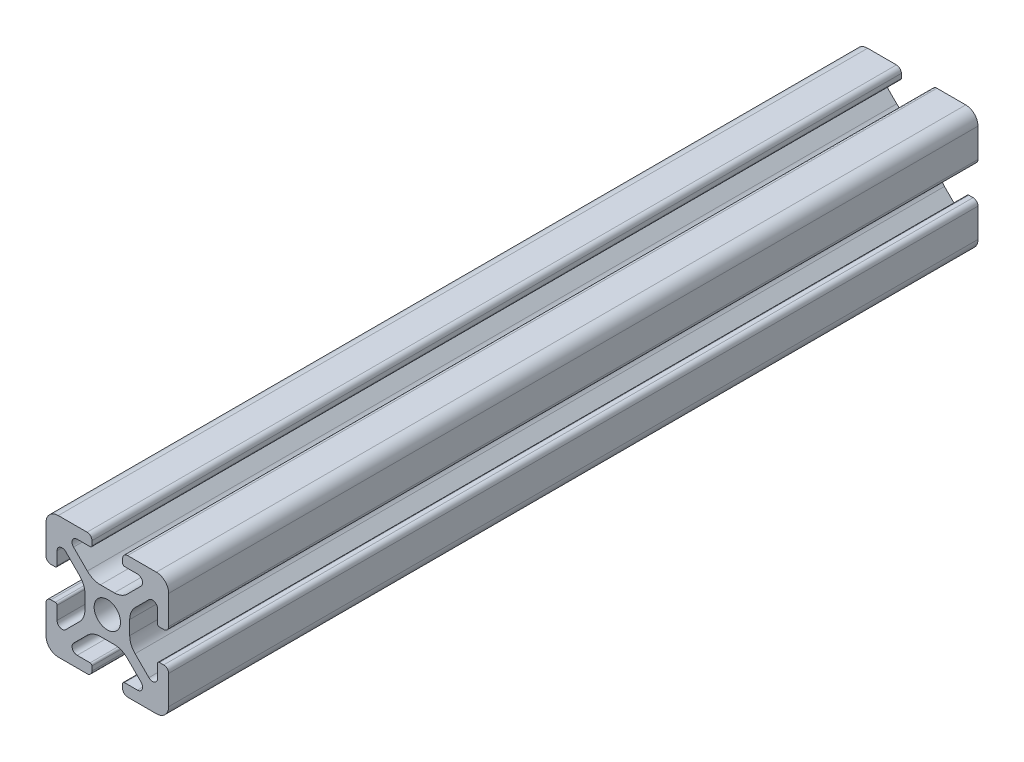
SolidWorks part; units mm, degrees
material "Alliage 1060"
ref_plane "Plan de face" through (0, 0, 0) normal (0, 0, 1) x (1, 0, 0)
ref_plane "Plan de dessus" through (0, 0, 0) normal (0, 1, 0) x (1, 0, 0)
ref_plane "Plan de droite" through (0, 0, 0) normal (1, 0, 0) x (0, 0, -1)
sketch "Esquisse1" plane through (0, 0, 0) normal (0, 0, 1) x (1, 0, 0)
  line L108 (-3.2559, 4.5287) -> (-5.5062, 6.779)
  line L109 (-4.9176, 8.2) -> (-2.8, 8.2)
  line L110 (-2.5, 8.5) -> (-2.5, 9.2)
  line L111 (-3.3, 10) -> (-8, 10)
  line L112 (-10, 8) -> (-10, 3.3)
  line L113 (-9.2, 2.5) -> (-8.5, 2.5)
  line L114 (-8.2, 2.8) -> (-8.2, 4.9176)
  line L115 (-6.779, 5.5062) -> (-4.5287, 3.2559)
  line L116 (-3.65, 1.1346) -> (-3.65, -1.1346)
  line L117 (-4.5287, -3.2559) -> (-6.779, -5.5062)
  line L118 (-8.2, -4.9176) -> (-8.2, -2.8)
  line L119 (-8.5, -2.5) -> (-9.2, -2.5)
  line L120 (-10, -3.3) -> (-10, -8)
  line L121 (-8, -10) -> (-3.3, -10)
  line L122 (-2.5, -9.2) -> (-2.5, -8.5)
  line L123 (-2.8, -8.2) -> (-4.9176, -8.2)
  line L124 (-5.5062, -6.779) -> (-3.2559, -4.5287)
  line L125 (-1.1346, -3.65) -> (1.1346, -3.65)
  line L126 (3.2559, -4.5287) -> (5.5062, -6.779)
  line L127 (4.9176, -8.2) -> (2.8, -8.2)
  line L128 (2.5, -8.5) -> (2.5, -9.2)
  line L129 (3.3, -10) -> (8, -10)
  line L130 (10, -8) -> (10, -3.3)
  line L131 (9.2, -2.5) -> (8.5, -2.5)
  line L132 (8.2, -2.8) -> (8.2, -4.9176)
  line L133 (6.779, -5.5062) -> (4.5287, -3.2559)
  line L134 (3.65, -1.1346) -> (3.65, 1.1346)
  line L135 (4.5287, 3.2559) -> (6.779, 5.5062)
  line L136 (8.2, 4.9176) -> (8.2, 2.8)
  line L137 (8.5, 2.5) -> (9.2, 2.5)
  line L138 (10, 3.3) -> (10, 8)
  line L139 (8, 10) -> (3.3, 10)
  line L140 (2.5, 9.2) -> (2.5, 8.5)
  line L141 (2.8, 8.2) -> (4.9176, 8.2)
  line L142 (5.5062, 6.779) -> (3.2559, 4.5287)
  line L143 (1.1346, 3.65) -> (-1.1346, 3.65)
  arc A42 (-2.15, 0) -> (2.15, 0) centre (0, 0) ccw
  arc A43 (2.15, 0) -> (-2.15, 0) centre (0, 0) ccw
  arc A108 (-4.9176, 8.2) -> (-5.5062, 6.779) centre (-4.9176, 7.3676) ccw
  arc A109 (-2.8, 8.2) -> (-2.5, 8.5) centre (-2.8, 8.5) ccw
  arc A110 (-2.5, 9.2) -> (-3.3, 10) centre (-3.3, 9.2) ccw
  arc A111 (-8, 10) -> (-10, 8) centre (-8, 8) ccw
  arc A112 (-10, 3.3) -> (-9.2, 2.5) centre (-9.2, 3.3) ccw
  arc A113 (-8.5, 2.5) -> (-8.2, 2.8) centre (-8.5, 2.8) ccw
  arc A114 (-6.779, 5.5062) -> (-8.2, 4.9176) centre (-7.3676, 4.9176) ccw
  arc A115 (-3.65, 1.1346) -> (-4.5287, 3.2559) centre (-6.65, 1.1346) ccw
  arc A116 (-4.5287, -3.2559) -> (-3.65, -1.1346) centre (-6.65, -1.1346) ccw
  arc A117 (-8.2, -4.9176) -> (-6.779, -5.5062) centre (-7.3676, -4.9176) ccw
  arc A118 (-8.2, -2.8) -> (-8.5, -2.5) centre (-8.5, -2.8) ccw
  arc A119 (-9.2, -2.5) -> (-10, -3.3) centre (-9.2, -3.3) ccw
  arc A120 (-10, -8) -> (-8, -10) centre (-8, -8) ccw
  arc A121 (-3.3, -10) -> (-2.5, -9.2) centre (-3.3, -9.2) ccw
  arc A122 (-2.5, -8.5) -> (-2.8, -8.2) centre (-2.8, -8.5) ccw
  arc A123 (-5.5062, -6.779) -> (-4.9176, -8.2) centre (-4.9176, -7.3676) ccw
  arc A124 (-1.1346, -3.65) -> (-3.2559, -4.5287) centre (-1.1346, -6.65) ccw
  arc A125 (3.2559, -4.5287) -> (1.1346, -3.65) centre (1.1346, -6.65) ccw
  arc A126 (4.9176, -8.2) -> (5.5062, -6.779) centre (4.9176, -7.3676) ccw
  arc A127 (2.8, -8.2) -> (2.5, -8.5) centre (2.8, -8.5) ccw
  arc A128 (2.5, -9.2) -> (3.3, -10) centre (3.3, -9.2) ccw
  arc A129 (8, -10) -> (10, -8) centre (8, -8) ccw
  arc A130 (10, -3.3) -> (9.2, -2.5) centre (9.2, -3.3) ccw
  arc A131 (8.5, -2.5) -> (8.2, -2.8) centre (8.5, -2.8) ccw
  arc A132 (6.779, -5.5062) -> (8.2, -4.9176) centre (7.3676, -4.9176) ccw
  arc A133 (3.65, -1.1346) -> (4.5287, -3.2559) centre (6.65, -1.1346) ccw
  arc A134 (4.5287, 3.2559) -> (3.65, 1.1346) centre (6.65, 1.1346) ccw
  arc A135 (8.2, 4.9176) -> (6.779, 5.5062) centre (7.3676, 4.9176) ccw
  arc A136 (8.2, 2.8) -> (8.5, 2.5) centre (8.5, 2.8) ccw
  arc A137 (9.2, 2.5) -> (10, 3.3) centre (9.2, 3.3) ccw
  arc A138 (10, 8) -> (8, 10) centre (8, 8) ccw
  arc A139 (3.3, 10) -> (2.5, 9.2) centre (3.3, 9.2) ccw
  arc A140 (2.5, 8.5) -> (2.8, 8.2) centre (2.8, 8.5) ccw
  arc A141 (5.5062, 6.779) -> (4.9176, 8.2) centre (4.9176, 7.3676) ccw
  arc A142 (1.1346, 3.65) -> (3.2559, 4.5287) centre (1.1346, 6.65) ccw
  arc A143 (-3.2559, 4.5287) -> (-1.1346, 3.65) centre (-1.1346, 6.65) ccw
extrude "Boss.-Extru.1" add sketch "Esquisse1" along normal blind 132
